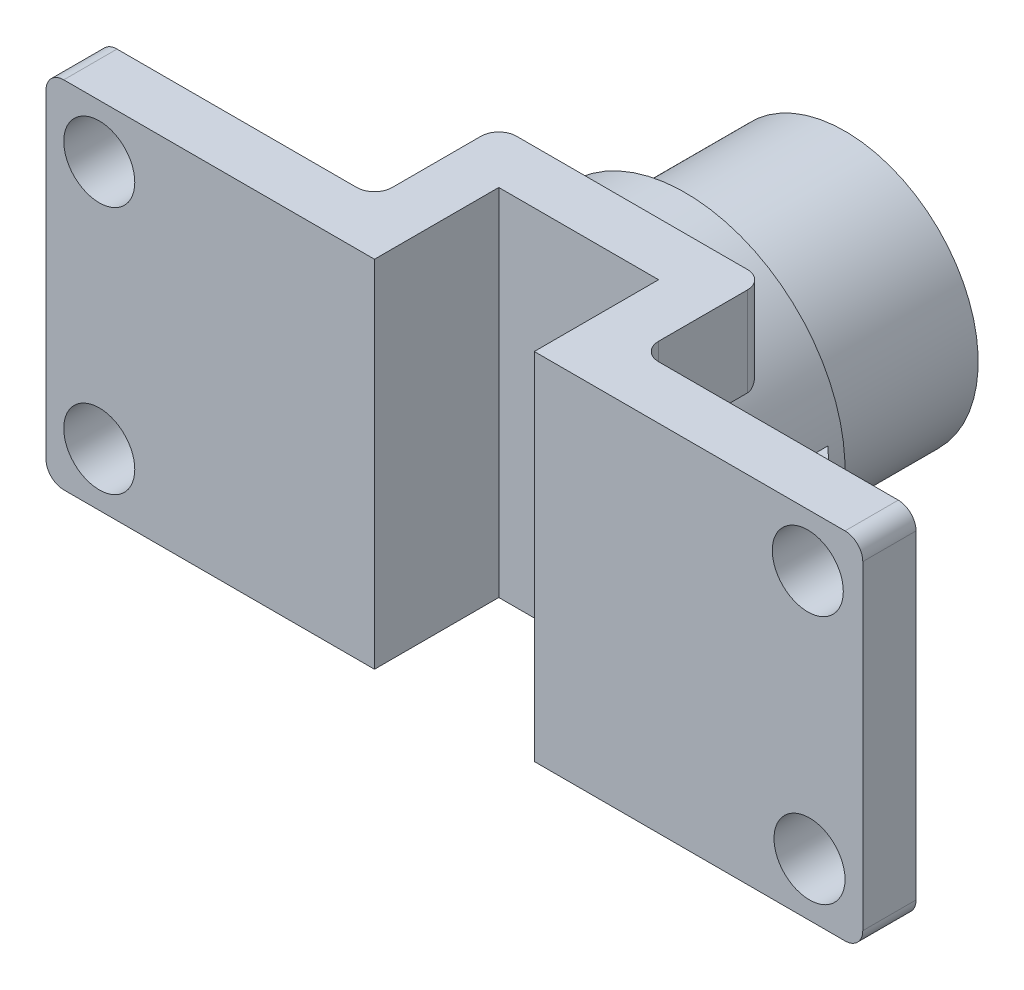
SolidWorks part; units mm, degrees
ref_plane "Front Plane" through (0, 0, 0) normal (0, 0, 1) x (1, 0, 0)
ref_plane "Top Plane" through (0, 0, 0) normal (0, 1, 0) x (1, 0, 0)
ref_plane "Right Plane" through (0, 0, 0) normal (1, 0, 0) x (0, 0, -1)
sketch "Sketch1" plane through (0, 0, 0) normal (0, 1, 0) x (1, 0, 0)
  line L0 (0, 0) -> (92, 0)
  line L1 (92, 0) -> (92, 6)
  line L2 (92, 6) -> (63, 6)
  line L3 (61, 8) -> (61, 18)
  line L4 (59, 20) -> (33, 20)
  line L5 (31, 18) -> (31, 8)
  line L6 (29, 6) -> (0, 6)
  line L7 (0, 6) -> (0, 0)
  line L8 (46, 20) -> (46, 0) construction
  arc A0 (63, 6) -> (61, 8) centre (63, 8) cw
  arc A1 (31, 8) -> (29, 6) centre (29, 8) cw
  arc A2 (33, 20) -> (31, 18) centre (33, 18) ccw
  arc A3 (61, 18) -> (59, 20) centre (59, 18) ccw
  point P17 (31, 20)
  point P20 (61, 20)
  dimension "D6" = 2
  dimension "D1" = 6
  dimension "D2" = 6
  dimension "D3" = 14
  dimension "D4" = 30
  dimension "D5" = 92
extrude "Boss-Extrude1" add sketch "Sketch1" along normal blind 40
ref_plane "Plane1" through (0, 0, -26) normal (0, 0, -1) x (-1, 0, 0)
sketch "Sketch2" plane through (0, 0, -26) normal (0, 0, -1) x (-1, 0, 0)
  line L0 (-46, 40) -> (-46, 0) construction
  line L1 (-59, 40) -> (-33, 40) construction
  line L2 (-59, 0) -> (-33, 0) construction
  circle A0 centre (-46, 20) radius 18
  dimension "D1" = 36
extrude "Boss-Extrude2" add sketch "Sketch2" against normal up to surface (20 mm away) up to face at (14.5, 20, -6)
sketch "Sketch3" plane through (0, 0, -26) normal (0, 0, -1) x (-1, 0, 0)
  circle A0 centre (-46, 20) radius 15
  circle A1 centre (-46, 20) radius 10
  dimension "D1" = 30
  dimension "D2" = 20
extrude "Boss-Extrude3" add sketch "Sketch3" along normal blind 18
ref_plane "Plane2" through (0, 20, 0) normal (0, -1, 0) x (-1, 0, 0)
sketch "Sketch4" plane through (0, 20, 0) normal (0, -1, 0) x (-1, 0, 0)
  line L0 (22, 26) -> (-22, 26) construction
  line L1 (-61.9867, 26) -> (-83, 6)
  line L2 (-92, 6) -> (-63, 6) construction
  line L3 (-83, 6) -> (-61.9867, 6)
  line L4 (-61.9867, 6) -> (-61.9867, 26)
  line L5 (-28.0355, 26) -> (-9, 6)
  line L6 (-29, 6) -> (0, 6) construction
  line L7 (-9, 6) -> (-28.0355, 6)
  line L8 (-28.0355, 6) -> (-28.0355, 26)
  dimension "D1" = 9
  dimension "D2" = 9
extrude "Boss-Extrude5" add sketch "Sketch4" along normal mid plane 6
sketch "Sketch5" plane through (28.0355, 0, 0) normal (1, 0, 0) x (0, 0, -1)
  line L4 (26, 18.8695) -> (6, 18.8695)
  line L5 (6, 18.8695) -> (6, 17)
  line L6 (6, 17) -> (26, 17)
  line L7 (26, 17) -> (26, 18.8695)
  line L8 (26, 18.8695) -> (6, 18.8695)
  line L9 (6, 18.8695) -> (6, 17)
  line L10 (6, 17) -> (26, 17)
  line L11 (26, 17) -> (26, 18.8695)
  dimension "D1" = 0
extrude "Boss-Extrude6" add sketch "Sketch5" along normal blind 6
sketch "Sketch6" plane through (28.0355, 0, 0) normal (1, 0, 0) x (0, 0, -1)
  line L4 (6, 21.1305) -> (26, 21.1305)
  line L5 (26, 21.1305) -> (26, 23)
  line L6 (26, 23) -> (6, 23)
  line L7 (6, 23) -> (6, 21.1305)
  line L8 (6, 21.1305) -> (26, 21.1305)
  line L9 (26, 21.1305) -> (26, 23)
  line L10 (26, 23) -> (6, 23)
  line L11 (6, 23) -> (6, 21.1305)
  dimension "D1" = 0
extrude "Boss-Extrude7" add sketch "Sketch6" along normal blind 6
ref_plane "Plane3" through (0, 60, 0) normal (0, 1, 0) x (1, 0, 0)
ref_plane "Plane4" through (0, 60, 0) normal (0, 1, 0) x (1, 0, 0)
sketch "Sketch8" plane through (0, 60, 0) normal (0, 1, 0) x (1, 0, 0)
  line L0 (0, 0) -> (92, 0) construction
  line L1 (37, 14) -> (55, 14)
  line L2 (37, 14) -> (37, 0)
  line L3 (37, 0) -> (55, 0)
  line L4 (55, 14) -> (55, 0)
  line L5 (37, 14) -> (55, 0) construction
  line L6 (37, 0) -> (55, 14) construction
  line L7 (59, 20) -> (33, 20) construction
  line L8 (61, 8) -> (61, 18) construction
  line L9 (31, 18) -> (31, 8) construction
  point P0 (46, 7)
  dimension "D1" = 6
  dimension "D2" = 6
  dimension "D3" = 6
extrude "Cut-Extrude1" cut sketch "Sketch8" against normal through all
fillet "Fillet1" radius 2 4 edges at (92, 40, -3) (92, 0, -3) (0, 0, -3) (0, 40, -3)
sketch "Sketch9" plane through (0, 0, 0) normal (0, 0, 1) x (1, 0, 0)
  line L0 (29, 0) -> (2, 0) construction
  line L1 (90, 0) -> (63, 0) construction
  line L2 (92, 38) -> (92, 2) construction
  line L3 (90, 40) -> (63, 40) construction
  line L4 (0, 38) -> (0, 2) construction
  line L5 (29, 40) -> (2, 40) construction
  circle A0 centre (86, 6) radius 4
  circle A1 centre (85.807, 34) radius 4
  circle A2 centre (6, 34) radius 4
  circle A3 centre (6, 6) radius 4
  dimension "D5" = 8
  dimension "D10" = 8
  dimension "D11" = 8
  dimension "D12" = 8
  dimension "D1" = 6
  dimension "D2" = 6
  dimension "D3" = 6
  dimension "D4" = 6.193
  dimension "D6" = 6
  dimension "D7" = 6
  dimension "D8" = 6
  dimension "D9" = 6
extrude "Cut-Extrude2" cut sketch "Sketch9" against normal blind 6
